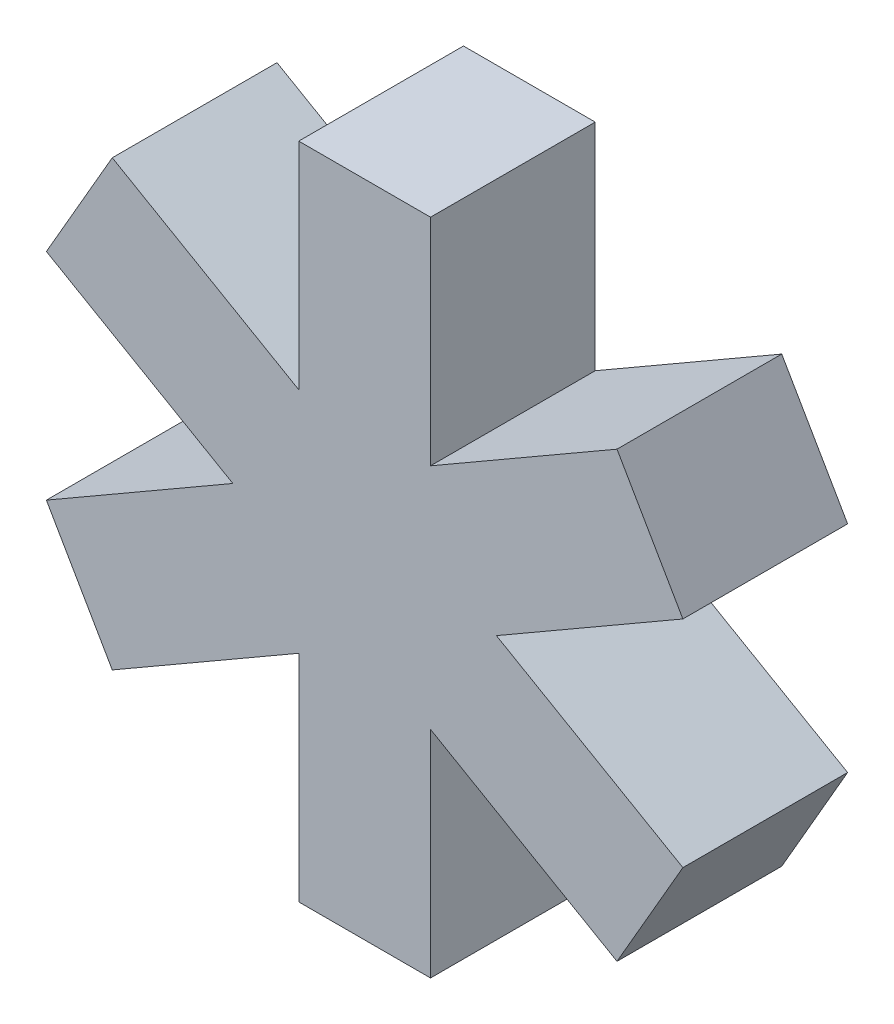
SolidWorks part; units mm, degrees
ref_plane "Спереди" through (0, 0, 0) normal (0, 0, 1) x (1, 0, 0)
ref_plane "Сверху" through (0, 0, 0) normal (0, 1, 0) x (1, 0, 0)
ref_plane "Справа" through (0, 0, 0) normal (1, 0, 0) x (0, 0, -1)
sketch "Эскиз1" plane through (0, 0, 0) normal (0, 0, 1) x (1, 0, 0)
  line L0 (-25.9808, 15) -> (25.9808, -15) construction
  line L7 (0, 30) -> (0, -30) construction
  line L8 (25.9808, 15) -> (-25.9808, -15) construction
  line L9 (-22.9808, 20.1962) -> (-28.9808, 9.8038)
  line L10 (-28.9808, 9.8038) -> (-12, 0)
  line L11 (-12, 0) -> (-28.9808, -9.8038)
  line L12 (-28.9808, -9.8038) -> (-22.9808, -20.1962)
  line L13 (-22.9808, -20.1962) -> (-6, -10.3923)
  line L14 (-6, -10.3923) -> (-6, -30)
  line L15 (-6, -30) -> (6, -30)
  line L16 (6, -30) -> (6, -10.3923)
  line L17 (6, -10.3923) -> (22.9808, -20.1962)
  line L18 (22.9808, -20.1962) -> (28.9808, -9.8038)
  line L19 (28.9808, -9.8038) -> (12, 0)
  line L20 (12, 0) -> (28.9808, 9.8038)
  line L21 (28.9808, 9.8038) -> (22.9808, 20.1962)
  line L22 (22.9808, 20.1962) -> (6, 10.3923)
  line L23 (6, 10.3923) -> (6, 30)
  line L24 (6, 30) -> (-6, 30)
  line L25 (-6, 30) -> (-6, 10.3923)
  line L26 (-6, 10.3923) -> (-22.9808, 20.1962)
  dimension "D1" = 60
  dimension "D2" = 60
  dimension "B" = 12
  dimension "D" = 60
extrude "Бобышка-Вытянуть1" add sketch "Эскиз1" along normal blind 15 contours L10 L11 L12 L13 L14 L15 L16 L17 L18 L19 L20 L21 L22 L23 L24 L25 L26 L9
